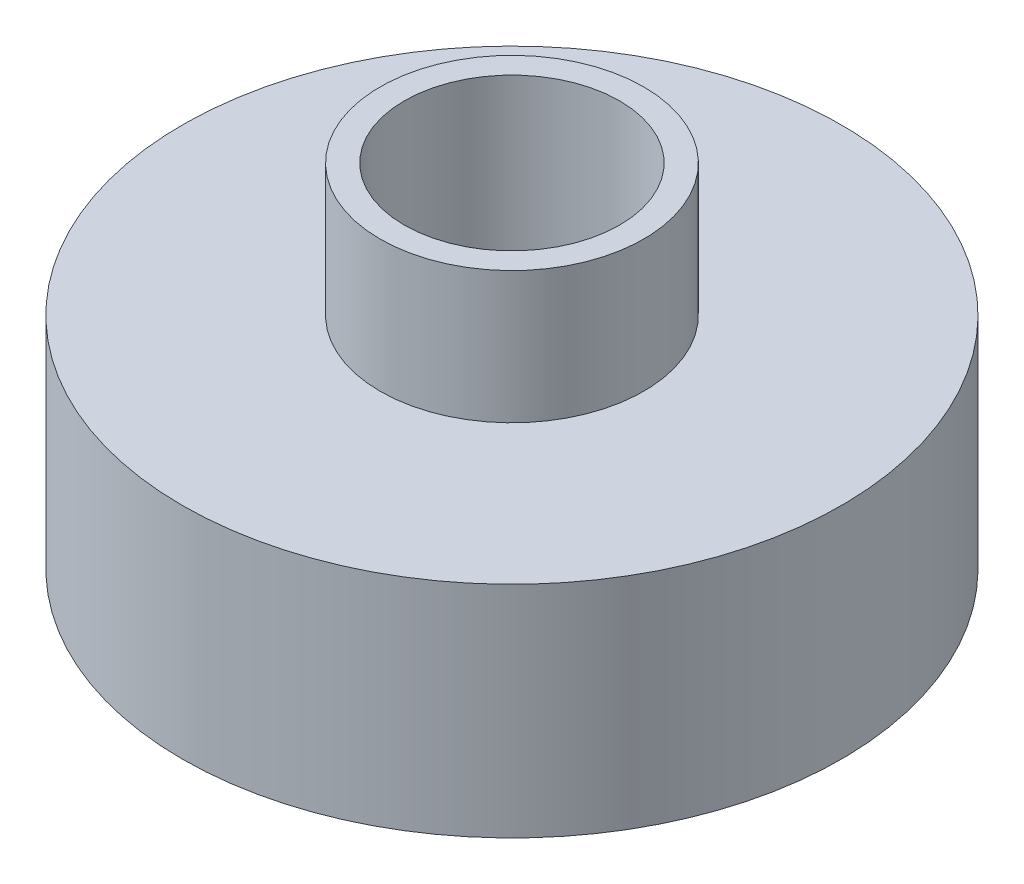
SolidWorks part; units mm, degrees
ref_plane "Front Plane" through (0, 0, 0) normal (0, 0, 1) x (1, 0, 0)
ref_plane "Top Plane" through (0, 0, 0) normal (0, 1, 0) x (1, 0, 0)
ref_plane "Right Plane" through (0, 0, 0) normal (1, 0, 0) x (0, 0, -1)
sketch "Sketch1" plane through (0, 0, 0) normal (0, 1, 0) x (1, 0, 0)
  circle A0 centre (0, 0) radius 9.525
  dimension "D1" = 19.05
extrude "Boss-Extrude1" add sketch "Sketch1" along normal blind 6.35
sketch "Sketch2" plane through (0, 6.35, 0) normal (0, 1, 0) x (1, 0, 0)
  circle A0 centre (0, 0) radius 3.81
  dimension "D1" = 7.62
extrude "Boss-Extrude2" add sketch "Sketch2" along normal blind 3.81
sketch "Sketch3" plane through (0, 10.16, 0) normal (0, 1, 0) x (1, 0, 0)
  circle A0 centre (0, 0) radius 3.1115
  dimension "D1" = 6.223
extrude "Cut-Extrude1" cut sketch "Sketch3" against normal blind 13.97
